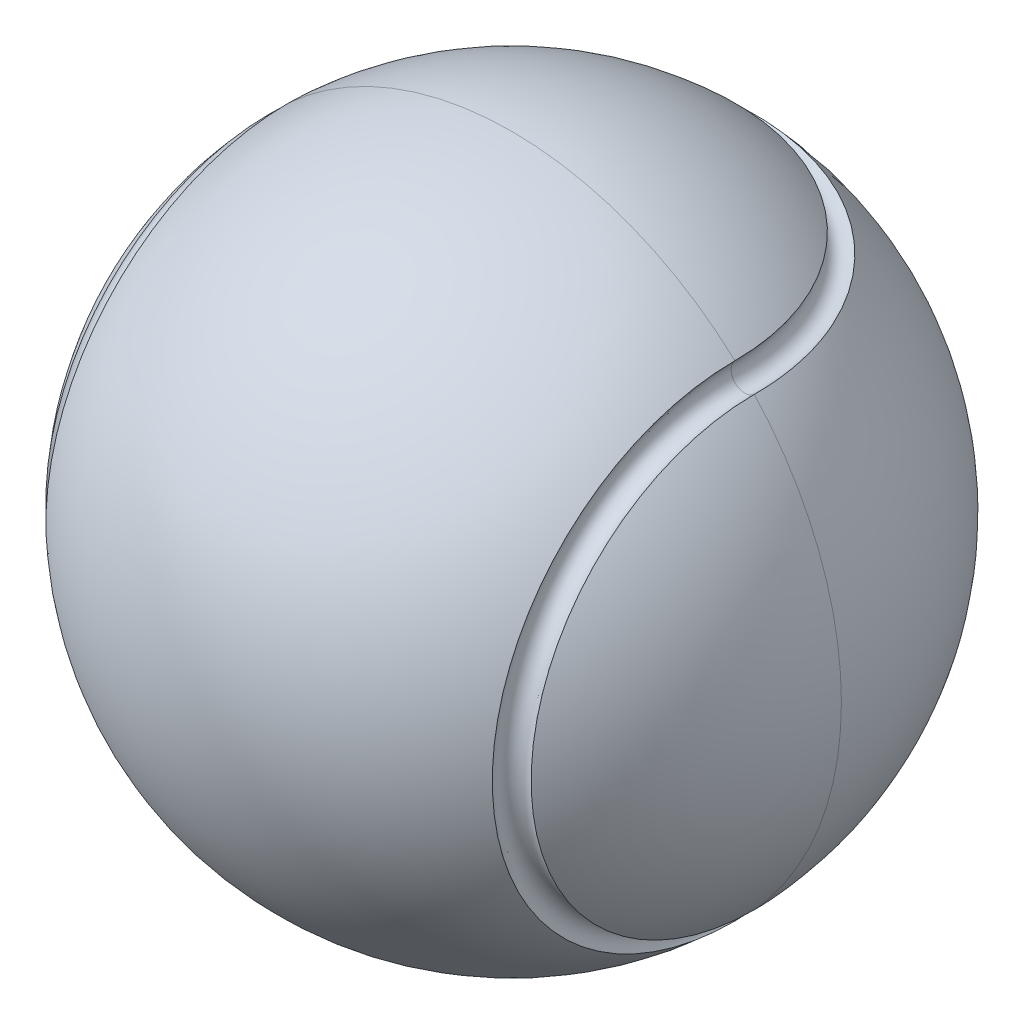
SolidWorks part; units mm, degrees
ref_plane "Front Plane" through (0, 0, 0) normal (0, 0, 1) x (1, 0, 0)
ref_plane "Top Plane" through (0, 0, 0) normal (0, 1, 0) x (1, 0, 0)
ref_plane "Right Plane" through (0, 0, 0) normal (1, 0, 0) x (0, 0, -1)
sketch "Sketch1" plane through (0, 0, 0) normal (0, 0, 1) x (1, 0, 0)
  line L0 (-76.2, 0) -> (76.2, 0)
  arc A0 (-76.2, 0) -> (76.2, 0) centre (0, 0) cw
  point P4 (0, 0)
  dimension "D1" = 152.4
  dimension "D2" = 76.2
revolve "Revolve1" add sketch "Sketch1" angle 360 about L0
sketch "Sketch3" plane through (0, 0, 0) normal (0, 0, 1) x (1, 0, 0)
  line L1 (-53.8815, -53.8815) -> (53.8815, -53.8815)
  line L2 (-53.8815, -53.8815) -> (-53.8815, 53.8815) construction
  line L3 (-53.8815, 53.8815) -> (53.8815, 53.8815) construction
  line L4 (53.8815, -53.8815) -> (53.8815, 53.8815) construction
  line L5 (-53.8815, -53.8815) -> (53.8815, 53.8815) construction
  line L6 (-53.8815, 53.8815) -> (53.8815, -53.8815) construction
  circle A0 centre (0, 0) radius 76.2 construction
  circle A1 centre (0, 0) radius 76.2
  point P7 (0, 0)
  point P8 (0, 0)
  point P9 (0, 0)
  point P10 (0, 0)
  point P11 (0, 0)
  point P12 (-53.8815, 0)
sketch "Sketch4" plane through (0, 0, 0) normal (0, 0, 1) x (1, 0, 0)
  line L0 (-53.8815, -53.8815) -> (53.8815, -53.8815) construction
  line L1 (-53.8815, -53.8815) -> (53.8815, -53.8815)
split line "Split Line2"
sketch "Sketch6" plane through (0, 0, 0) normal (0, 0, 1) x (1, 0, 0)
  line L0 (-53.8815, -53.8815) -> (53.8815, -53.8815) construction
  line L1 (-53.8815, -53.8815) -> (53.8815, -53.8815)
  line L2 (-53.8815, -53.8815) -> (-53.8815, 53.8815) construction
  line L3 (-53.8815, -53.8815) -> (-53.8815, 53.8815)
  circle A1 centre (0, 0) radius 76.2
  circle A2 centre (0, 0) radius 76.2
  point P5 (0, 0)
  dimension "D1" = 0
sketch "Sketch7" plane through (0, 0, 0) normal (0, 0, 1) x (1, 0, 0)
  line L0 (-53.8815, -53.8815) -> (-53.8815, 53.8815) construction
  line L1 (-53.8815, -53.8815) -> (-53.8815, 53.8815)
curve "Curve4"
sketch "Sketch8" plane through (0, 0, 0) normal (0, 0, 1) x (1, 0, 0)
  line L0 (-53.8815, 53.8815) -> (53.8815, 53.8815) construction
  line L1 (-53.8815, 53.8815) -> (53.8815, 53.8815)
split line "Split Line4"
sketch "Sketch9" plane through (0, 0, 0) normal (0, 0, 1) x (1, 0, 0)
  line L0 (53.8815, -53.8815) -> (53.8815, 53.8815) construction
  line L1 (53.8815, -53.8815) -> (53.8815, 53.8815)
curve "Curve5"
curve "CompCurve1"
sweep "Cut-Sweep1" cut path "CompCurve1" circular profile diameter 6.35 parameters "D3"=6.35
